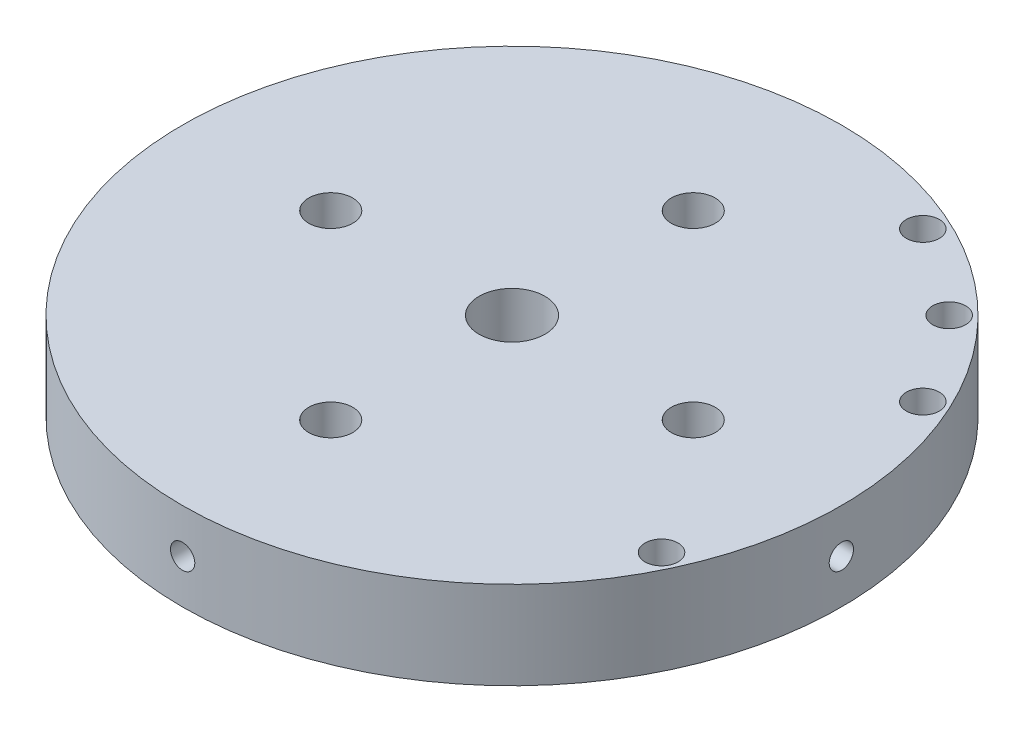
SolidWorks part; units mm, degrees
ref_plane "Front Plane" through (0, 0, 0) normal (0, 0, 1) x (1, 0, 0)
ref_plane "Top Plane" through (0, 0, 0) normal (0, 1, 0) x (1, 0, 0)
ref_plane "Right Plane" through (0, 0, 0) normal (1, 0, 0) x (0, 0, -1)
sketch "Sketch1" plane through (0, 0, 0) normal (0, 1, 0) x (1, 0, 0)
  circle A0 centre (0, 0) radius 47.625
  dimension "D1" = 95.25
extrude "Boss-Extrude1" add sketch "Sketch1" along normal blind 12.7
ref_plane "Plane1" through (-47.625, 0, 0) normal (-1, 0, 0) x (0, 0, 1)
ref_plane "Plane2" through (0, 0, -47.625) normal (0, 0, -1) x (0, -1, 0)
sketch "Sketch6" plane through (0, 0, -47.625) normal (0, 0, -1) x (0, -1, 0)
  line L0 (0, 0) -> (-12.7, 0) construction
  line L1 (-12.7, 47.625) -> (-12.7, -47.625) construction
  line L2 (-6.35, 47.625) -> (-6.35, -47.625) construction
  line L3 (0, 47.625) -> (-12.7, 47.625) construction
  line L4 (-12.7, -47.625) -> (0, -47.625) construction
  circle A0 centre (-6.35, 0) radius 1.7526
  dimension "D1" = 3.5052
extrude "Cut-Extrude3" cut sketch "Sketch6" against normal blind 19.05 contours A0
pattern_circular "CirPattern4" count 4 over 360 about axis through (0, 0, 0) along (0, 1, 0) of "Cut-Extrude3"
ref_plane "Plane5" through (47.625, 0, 0) normal (1, 0, 0) x (0, -1, 0)
ref_plane "Plane7" through (-47.625, 0, 0) normal (-1, 0, 0) x (0, -1, 0)
ref_plane "Plane9" through (-33.676, 0, 33.676) normal (-0.7071, 0, 0.7071) x (0, -1, 0)
sketch "Sketch7" plane through (0, 0, 0) normal (0, 1, 0) x (1, 0, 0)
  line L0 (0, 0) -> (47.625, 0) construction
  line L1 (47.625, 0) -> (0, 0) construction
  line L2 (0, 0) -> (-47.625, 0) construction
  line L3 (-47.625, 6.985) -> (-47.625, -6.985) construction
  line L4 (0, 0) -> (0, 47.625) construction
  line L5 (0, 47.625) -> (0, -47.625) construction
  circle A0 centre (0, 0) radius 47.625 construction
  circle A1 centre (-26.1937, 0) radius 3.175
  circle A2 centre (26.1937, 0) radius 3.175
  circle A3 centre (0, 26.1937) radius 3.175
  circle A4 centre (0, -26.1937) radius 3.175
  dimension "D5" = 6.35
  dimension "D1" = 26.1937
  dimension "D2" = 52.3875
  dimension "D3" = 26.1937
  dimension "D4" = 52.3875
extrude "Cut-Extrude6" cut sketch "Sketch7" along normal through all
sketch "Sketch8" plane through (0, 12.7, 0) normal (0, 1, 0) x (1, 0, 0)
  circle A0 centre (0, 0) radius 4.7625
  dimension "D1" = 9.525
extrude "Cut-Extrude7" cut sketch "Sketch8" against normal through all
sketch "Sketch11" plane through (0, 12.7, 0) normal (0, 1, 0) x (1, 0, 0)
  line L0 (0, 0) -> (31.589, 31.589) construction
  line L1 (0, 0) -> (40.488, 18.8799) construction
  line L2 (0, 0) -> (18.8799, 40.488) construction
  line L3 (0, 0) -> (40.488, -18.8799) construction
  circle A0 centre (31.589, 31.589) radius 2.3812
  circle A1 centre (40.488, 18.8799) radius 2.3812
  circle A2 centre (18.8799, 40.488) radius 2.3813
  circle A3 centre (40.488, -18.8799) radius 2.3812
  dimension "D1" = 4.7625
  dimension "D2" = 4.7625
  dimension "D4" = 4.7625
  dimension "D6" = 4.7625
  dimension "D3" = 20
  dimension "D5" = 20
  dimension "D7" = 50
extrude "Cut-Extrude8" cut sketch "Sketch11" against normal through all
